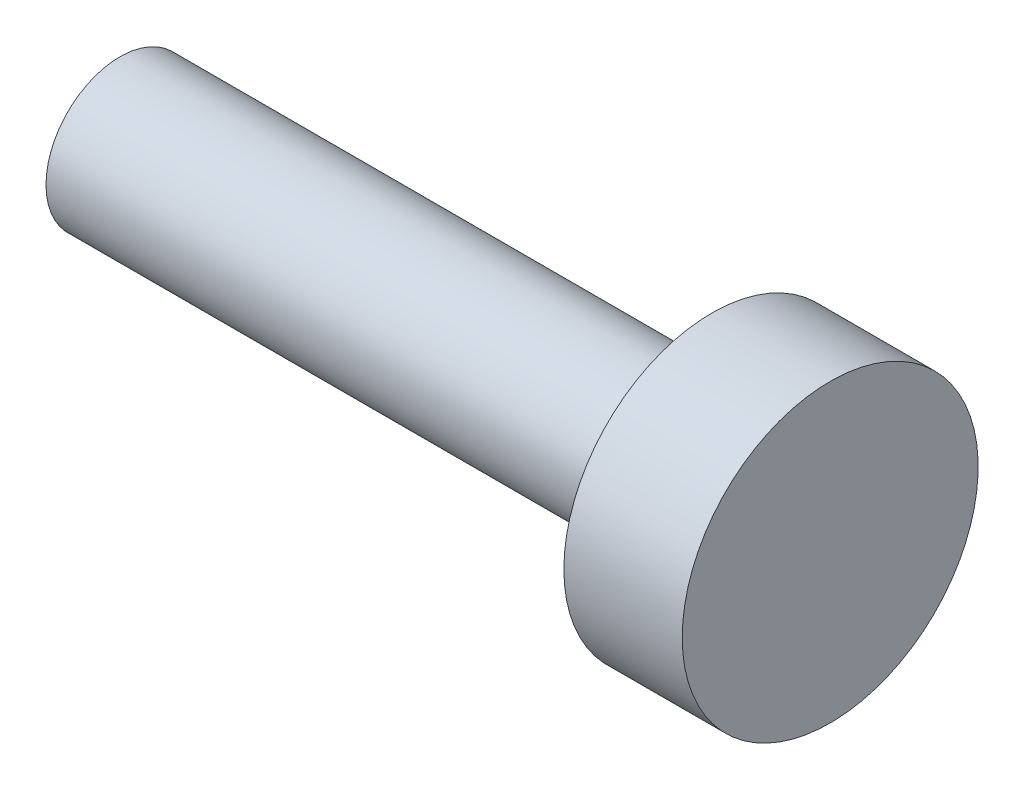
SolidWorks part; units mm, degrees
ref_plane "Přední rovina" through (0, 0, 0) normal (0, 0, 1) x (1, 0, 0)
ref_plane "Horní rovina" through (0, 0, 0) normal (0, 1, 0) x (1, 0, 0)
ref_plane "Pravá rovina" through (0, 0, 0) normal (1, 0, 0) x (0, 0, -1)
sketch "Skica1" plane through (0, 0, 0) normal (0, 0, 1) x (1, 0, 0)
  line L0 (0, 0) -> (12, 0) construction
  line L2 (12, 2.5) -> (10, 2.5)
  line L3 (10, 2.5) -> (10, 1.25)
  line L4 (10, 1.25) -> (0, 1.25)
  line L9 (12, 0) -> (12, 2.5)
  line L10 (0, 0) -> (0, 1.25)
  line L11 (0, 0) -> (12, 0)
  dimension "D1" = 5
  dimension "D2" = 2.5
  dimension "D3" = 2
  dimension "D4" = 12
revolve "Rotovat3" add sketch "Skica1" angle 360 about L0
